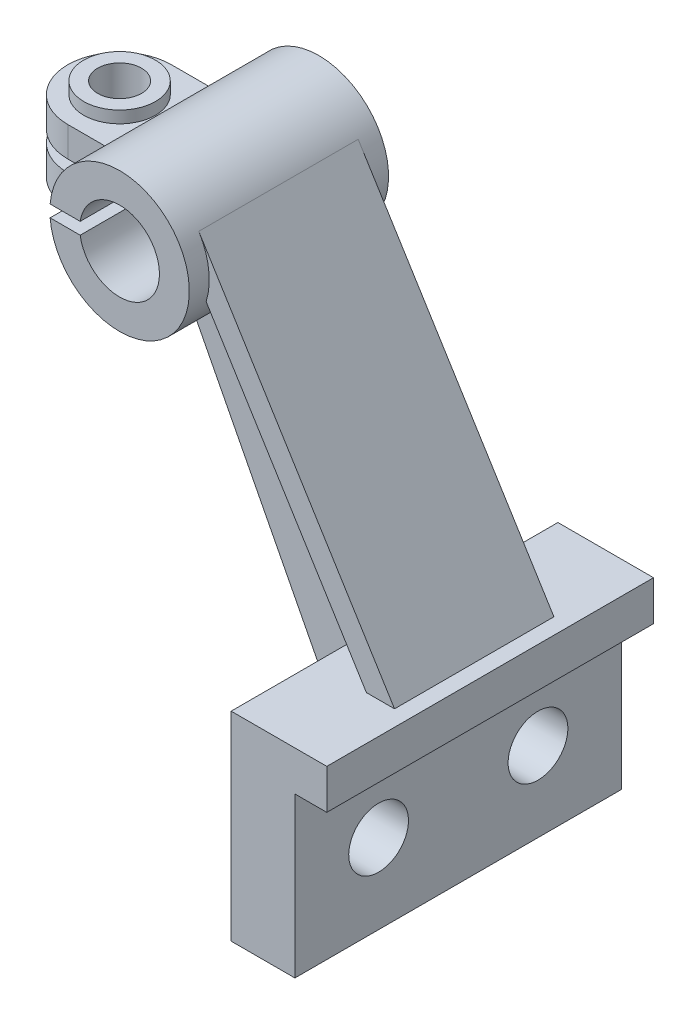
SolidWorks part; units mm, degrees
ref_plane "前视基准面" through (0, 0, 0) normal (0, 0, 1) x (1, 0, 0)
ref_plane "上视基准面" through (0, 0, 0) normal (0, 1, 0) x (1, 0, 0)
ref_plane "右视基准面" through (0, 0, 0) normal (1, 0, 0) x (0, 0, -1)
sketch "草图1" plane through (0, 0, 0) normal (0, 0, 1) x (1, 0, 0)
  circle A0 centre (0, 0) radius 17.5
  dimension "D1" = 35
extrude "凸台-拉伸1" add sketch "草图1" along normal mid plane 50
sketch "草图2" plane through (0, 0, 0) normal (0, 1, 0) x (1, 0, 0)
  line L0 (0, 0) -> (-25, 0) construction
  line L1 (-19.25, 0) -> (19.25, 0) construction
  line L2 (0, -13) -> (-25, -13)
  line L3 (0, 13) -> (-25, 13)
  arc A0 (0, -13) -> (0, 13) centre (0, 0) ccw
  arc A1 (-25, 13) -> (-25, -13) centre (-25, 0) ccw
  point P5 (-12.5, 0)
  dimension "D1" = 13
  dimension "D2" = 25
extrude "凸台-拉伸2" add sketch "草图2" along normal mid plane 18
sketch "草图3" plane through (0, 9, 0) normal (0, 1, 0) x (1, 0, 0)
  circle A0 centre (-25, 0) radius 9
  dimension "D1" = 18
extrude "凸台-拉伸3" add sketch "草图3" along normal blind 3
sketch "草图4" plane through (0, 0, 0) normal (0, 0, 1) x (1, 0, 0)
  line L1 (-40.7776, -1.5) -> (0, -1.5)
  line L2 (-40.7776, -1.5) -> (-40.7776, 1.5)
  line L3 (-40.7776, 1.5) -> (0, 1.5)
  line L4 (0, -1.5) -> (0, 1.5)
  line L5 (-40.7776, -1.5) -> (0, 1.5) construction
  line L6 (-40.7776, 1.5) -> (0, -1.5) construction
  point P0 (-20.3888, 0)
  dimension "D1" = 3
extrude "切除-拉伸1" cut sketch "草图4" against normal through all both and the other way through all
sketch "草图5" plane through (0, 0, 25) normal (0, 0, 1) x (1, 0, 0)
  circle A0 centre (0, 0) radius 10
  dimension "D1" = 20
extrude "切除-拉伸2" cut sketch "草图5" against normal through all both and the other way through all
sketch "草图6" plane through (0, 12, 0) normal (0, 1, 0) x (1, 0, 0)
  circle A0 centre (-25, 0) radius 5.5
  dimension "D1" = 11
extrude "切除-拉伸3" cut sketch "草图6" against normal up to next
sketch "草图7" plane through (0, -1.5, 0) normal (0, 1, 0) x (1, 0, 0)
  point P0 (-25, 0)
hole_wizard "M10 螺纹孔1" positions "草图7" profile "草图8" tap size "M10" standard "GB" end condition up to next
sketch "草图8" plane through (-25, -1.5, 0) normal (1, 0, 0) x (0, 0, 1)
  line L0 (0, 0) -> (0, 7.5)
  line L1 (0, 7.5) -> (4.25, 7.5)
  line L2 (4.25, 7.5) -> (4.25, 0)
  line L5 (4.25, 0) -> (0, 0)
  line L11 (0, -6.35) -> (0, 107.95) construction
  dimension "通孔螺纹孔钻头直径" = 8.5
  dimension "通孔螺纹孔钻头深度" = 7.5
cosmetic thread "孔螺纹线1" parameters "D2"=10
sketch "草图9" plane through (0, 0, 0) normal (0, 0, 1) x (1, 0, 0)
  line L1 (44, -70) -> (60, -70)
  line L2 (44, -70) -> (44, -120)
  line L3 (44, -120) -> (60, -120)
  line L4 (60, -70) -> (60, -120)
  point P4 (52, -70)
  dimension "D1" = 16
  dimension "D2" = 50
  dimension "D3" = 60
  dimension "D4" = 70
extrude "凸台-拉伸4" add sketch "草图9" along normal mid plane 82 separate body
sketch "草图10" plane through (60, 0, 0) normal (1, 0, 0) x (0, 0, -1)
  line L0 (41, -120) -> (41, -70) construction
  line L1 (-41, -70) -> (41, -70)
  line L2 (-41, -70) -> (-41, -80)
  line L3 (-41, -80) -> (41, -80)
  line L4 (41, -70) -> (41, -80)
  dimension "D1" = 10
extrude "凸台-拉伸5" add sketch "草图10" along normal blind 8
sketch "草图11" plane through (0, 0, 0) normal (0, 0, 1) x (1, 0, 0)
  line L0 (-7, -16.039) -> (44, -115)
  line L1 (44, -70) -> (44, -120) construction
  line L2 (44, -120) -> (60, -120) construction
  line L3 (14.8725, 9.2227) -> (64, -70)
  line L4 (68, -70) -> (44, -70) construction
  line L5 (68, -70) -> (68, -80) construction
  line L6 (44, -115) -> (44, -70)
  line L7 (44, -70) -> (64, -70)
  arc A0 (-17.4356, -1.5) -> (-17.4356, 1.5) centre (0, 0) ccw construction
  arc A1 (-7, -16.039) -> (14.8725, 9.2227) centre (0, 0) ccw
  dimension "D1" = 7
  dimension "D2" = 5
  dimension "D3" = 4
extrude "凸台-拉伸6" add sketch "草图11" along normal mid plane 8
sketch "草图12" plane through (0, 0, 0) normal (0, 0, 1) x (1, 0, 0)
  line L0 (64, -70) -> (14.8725, 9.2227) construction
  line L1 (64, -70) -> (14.8725, 9.2227)
  line L2 (56.94, -70) -> (16.7251, -5.1497)
  line L3 (58.9009, -73.1621) -> (9.7734, 6.0606) construction
  line L4 (64, -70) -> (56.94, -70)
  line L5 (44, -70) -> (64, -70) construction
  arc A0 (-17.4356, -1.5) -> (-17.4356, 1.5) centre (0, 0) ccw construction
  arc A1 (16.7251, -5.1497) -> (14.8725, 9.2227) centre (0, 0) ccw
  dimension "D1" = 6
extrude "凸台-拉伸7" add sketch "草图12" along normal mid plane 40
sketch "草图13" plane through (44, 0, 0) normal (-1, 0, 0) x (0, 0, 1)
  line L0 (-41, -120) -> (-41, -80) construction
  line L1 (-41, -120) -> (-41, -80) construction
  circle A0 centre (-20, -100) radius 14
  point P5 (-41, -100)
  dimension "D1" = 28
  dimension "D2" = 20
extrude "切除-拉伸4" cut sketch "草图13" against normal blind 3
sketch "草图14" plane through (47, 0, 0) normal (-1, 0, 0) x (0, 0, 1)
  circle A0 centre (-20, -100) radius 7.5
  dimension "D1" = 15
extrude "切除-拉伸5" cut sketch "草图14" against normal through all
mirror "镜向1" about plane through (0, 0, 0) normal (0, 0, 1) of "切除-拉伸4", "切除-拉伸5"
